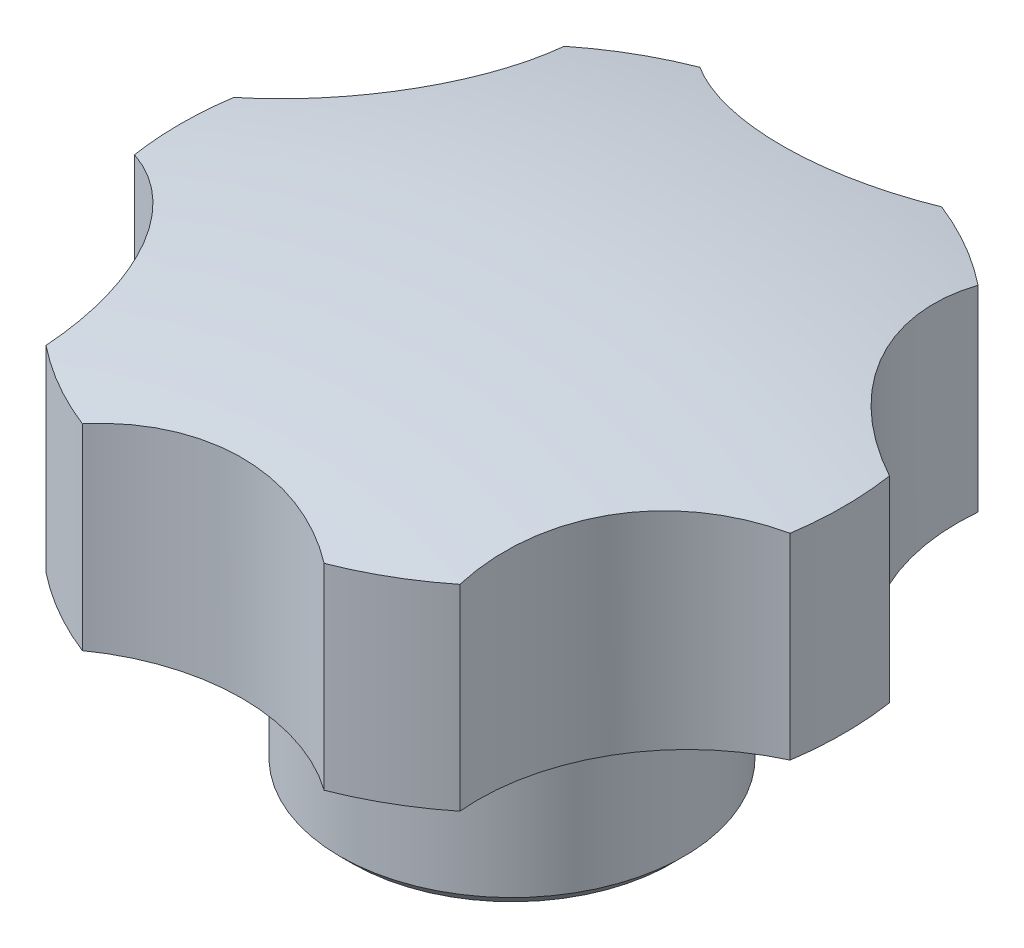
SolidWorks part; units mm, degrees
ref_plane "前视基准面" through (0, 0, 0) normal (0, 0, 1) x (1, 0, 0)
ref_plane "上视基准面" through (0, 0, 0) normal (0, 1, 0) x (1, 0, 0)
ref_plane "右视基准面" through (0, 0, 0) normal (1, 0, 0) x (0, 0, -1)
other "Configuration Table"
sketch "草图1" plane through (0, 0, 0) normal (0, 0, 1) x (1, 0, 0)
  line L0 (0, 17.5) -> (0, -17.5)
  line L1 (0, -17.5) -> (-14, -17.5)
  line L2 (-14, -17.5) -> (-14, -3.3348)
  line L3 (-16, -1.3348) -> (-27, -1.3348)
  line L4 (-27, -1.3348) -> (-27, 14.6652)
  line L5 (0, 51.0945) -> (0, -45.252) construction
  arc A0 (-14, -3.3348) -> (-16, -1.3348) centre (-16, -3.3348) ccw
  arc A1 (-27, 14.6652) -> (0, 17.5) centre (0, -112.5) cw
  point P13 (0, 0)
  dimension "D2" = 2
  dimension "D4" = 130
  dimension "D1" = 28
  dimension "D3" = 16
  dimension "D5" = 35
  dimension "D6" = 17.5
  dimension "D7" = 54
revolve "旋转1" add sketch "草图1" angle 360 about L5
chamfer "倒角1" distance 1 angle 45 1 edges at (0, -17.5, 14)
sketch "草图3" plane through (0, -1.3348, 0) normal (0, -1, 0) x (1, 0, 0)
  line L0 (0, 34.8166) -> (0, -32.5025) construction
  circle A0 centre (0, 0) radius 22
  arc A1 (-9.8452, 25.141) -> (9.8452, 25.141) centre (0, 39) ccw
  circle A2 centre (0, 0) radius 27 construction
  arc A3 (9.8452, 25.141) -> (-9.8452, 25.141) centre (0, 0) ccw
  point P10 (0, 0)
  circle M4 centre (0, 0) radius 27
  dimension "D1" = 44
  dimension "D2" = 17
extrude "切除-拉伸1" cut sketch "草图3" against normal through all contours L0 A1 M4 | L0 A3 A1
pattern_circular "阵列(圆周)1" count 6 over 360 about axis through (0, 0, 0) along (0, 1, 0) of "切除-拉伸1"
hole_wizard "大小mm 暗销孔1" positions "草图4" profile "草图5" hole size "Ø10.0" standard "GB"
sketch "草图4" plane through (0, -17.5, 0) normal (0, -1, 0) x (-1, 0, 0)
  point P0 (0, 0)
sketch "草图5" plane through (0, -17.5, 0) normal (1, 0, 0) x (0, 0, -1)
  line L0 (0, 0) -> (0, 23.0043)
  line L1 (0, 23.0043) -> (5, 20)
  line L2 (5, 20) -> (5, 0)
  line L5 (5, 0) -> (0, 0)
  line L10 (0, 23.0043) -> (-5, 20) construction
  line L11 (0, -6.35) -> (0, 107.95) construction
  dimension "孔直径" = 10
  dimension "孔深度" = 20
  dimension "导头角度" = 118
